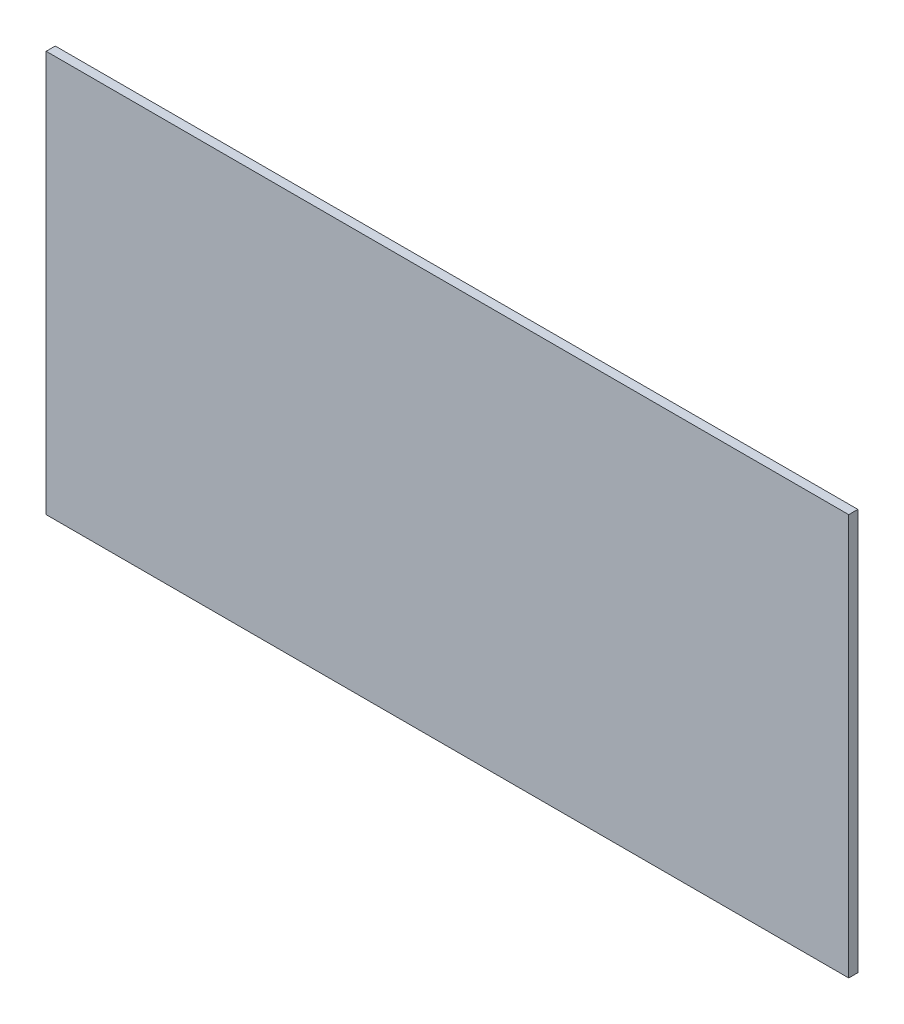
SolidWorks part; units mm, degrees
ref_plane "Plan de face" through (0, 0, 0) normal (0, 0, 1) x (1, 0, 0)
ref_plane "Plan de dessus" through (0, 0, 0) normal (0, 1, 0) x (1, 0, 0)
ref_plane "Plan de droite" through (0, 0, 0) normal (1, 0, 0) x (0, 0, -1)
sketch "Esquisse1" plane through (0, 0, 0) normal (0, 0, 1) x (1, 0, 0)
  line L0 (-357.0726, 0) -> (397.0592, 0) construction
  line L1 (0, 264.1563) -> (0, -245.5525) construction
  line L2 (-220, 110) -> (-220, -110)
  line L3 (-220, -110) -> (220, -110)
  line L4 (220, -110) -> (220, 110)
  line L5 (220, 110) -> (-220, 110)
  point P5 (0, 0)
  point P8 (0, 0)
  dimension "D1" = 440
  dimension "D2" = 220
extrude "Boss.-Extru.3" add sketch "Esquisse1" along normal blind 5
